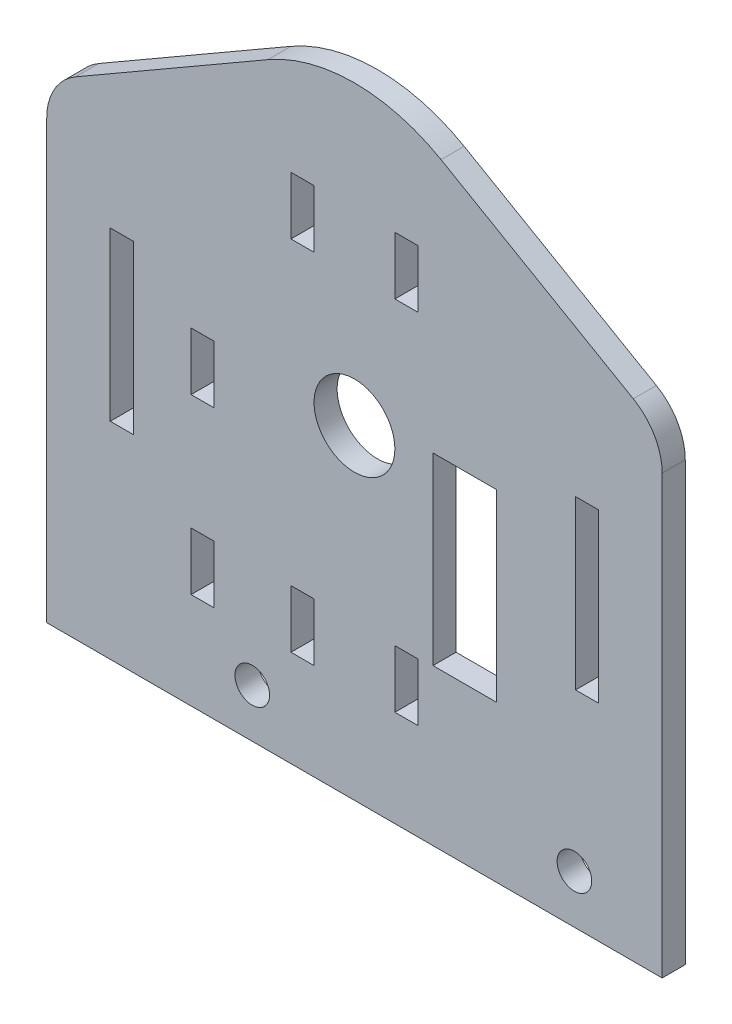
SolidWorks part; units mm, degrees
ref_plane "Front Plane" through (0, 0, 0) normal (0, 0, 1) x (1, 0, 0)
ref_plane "Top Plane" through (0, 0, 0) normal (0, 1, 0) x (1, 0, 0)
ref_plane "Right Plane" through (0, 0, 0) normal (1, 0, 0) x (0, 0, -1)
sketch "Sketch1" plane through (0, 0, 0) normal (0, 0, 1) x (1, 0, 0)
  line L0 (0, 116.93) -> (0, 0) construction
  line L1 (-25.65, 0) -> (25.65, 0)
  line L2 (-26.65, 0) -> (-26.65, 116.93) construction
  line L3 (-26.65, 116.93) -> (26.65, 116.93) construction
  line L4 (26.65, 0) -> (26.65, 116.93) construction
  line L5 (24.15, 104.0845) -> (7.5, 113.6974)
  line L6 (3.5, 106.25) -> (5.5, 106.25)
  line L7 (3.5, 106.25) -> (3.5, 101.25)
  line L8 (3.5, 101.25) -> (5.5, 101.25)
  line L9 (5.5, 106.25) -> (5.5, 101.25)
  line L10 (6.8, 91.35) -> (12.3, 91.35)
  line L11 (6.8, 91.35) -> (6.8, 75.4)
  line L12 (6.8, 75.4) -> (12.3, 75.4)
  line L13 (12.3, 91.35) -> (12.3, 75.4)
  line L14 (19.15, 94.25) -> (21.15, 94.25)
  line L15 (19.15, 94.25) -> (19.15, 79.75)
  line L16 (19.15, 79.75) -> (21.15, 79.75)
  line L17 (21.15, 94.25) -> (21.15, 79.75)
  line L18 (3.5, 75.25) -> (5.5, 75.25)
  line L19 (3.5, 75.25) -> (3.5, 70.25)
  line L20 (3.5, 70.25) -> (5.5, 70.25)
  line L21 (5.5, 75.25) -> (5.5, 70.25)
  line L22 (-7.5, 113.6974) -> (-24.15, 104.0845)
  line L23 (-26.65, 99.7544) -> (-26.65, 1)
  line L24 (26.65, 1) -> (26.65, 99.7544)
  line L25 (-5.5, 75.25) -> (-5.5, 70.25)
  line L26 (-3.5, 75.25) -> (-3.5, 70.25)
  line L27 (-3.5, 75.25) -> (-5.5, 75.25)
  line L28 (-3.5, 70.25) -> (-5.5, 70.25)
  line L29 (-19.15, 94.25) -> (-21.15, 94.25)
  line L30 (-19.15, 79.75) -> (-21.15, 79.75)
  line L31 (-21.15, 94.25) -> (-21.15, 79.75)
  line L32 (-19.15, 94.25) -> (-19.15, 79.75)
  line L33 (-3.5, 101.25) -> (-5.5, 101.25)
  line L34 (-3.5, 106.25) -> (-5.5, 106.25)
  line L35 (-3.5, 106.25) -> (-3.5, 101.25)
  line L36 (-5.5, 106.25) -> (-5.5, 101.25)
  line L37 (-21.15, 92.25) -> (-5.8071, 92.25) construction
  line L38 (-12.15, 70.25) -> (-14.15, 70.25)
  line L39 (-12.15, 70.25) -> (-12.15, 75.25)
  line L40 (-12.15, 75.25) -> (-14.15, 75.25)
  line L41 (-14.15, 70.25) -> (-14.15, 75.25)
  line L42 (-14.15, 85.25) -> (-12.15, 85.25)
  line L43 (-14.15, 85.25) -> (-14.15, 90.25)
  line L44 (-14.15, 90.25) -> (-12.15, 90.25)
  line L45 (-12.15, 85.25) -> (-12.15, 90.25)
  line L46 (-21.15, 82.4202) -> (-6.2517, 82.4202) construction
  line L47 (-8.85, 66.1) -> (19.05, 66.1) construction
  line L48 (0, 34.3) -> (-24.05, 34.3) construction
  line L49 (-20, 34.3) -> (-20, 36.05)
  line L50 (-7, 36.05) -> (-20, 36.05)
  line L51 (-7, 36.05) -> (-7, 34.3)
  line L52 (-7, 34.3) -> (-7, 32.55)
  line L53 (-7, 32.55) -> (-20, 32.55)
  line L54 (-20, 32.55) -> (-20, 34.3)
  line L55 (0, 34.3) -> (-13.6195, 57.8897) construction
  line L56 (-5.2321, 39.3622) -> (-15.7321, 57.5487)
  line L57 (-15.7321, 57.5487) -> (-12.2679, 59.5487)
  line L58 (-12.2679, 59.5487) -> (-1.7679, 41.3622)
  line L59 (-1.7679, 41.3622) -> (-5.2321, 39.3622)
  line L60 (-14, 58.5487) -> (-3.5, 40.3622) construction
  line L61 (1.7679, 41.3622) -> (5.2321, 39.3622)
  line L62 (15.7321, 57.5487) -> (12.2679, 59.5487)
  line L63 (12.2679, 59.5487) -> (1.7679, 41.3622)
  line L64 (5.2321, 39.3622) -> (15.7321, 57.5487)
  line L65 (7, 34.3) -> (7, 32.55)
  line L78 (7, 36.05) -> (7, 34.3)
  line L131 (7, 32.55) -> (20, 32.55)
  line L132 (20, 32.55) -> (20, 34.3)
  line L133 (20, 34.3) -> (20, 36.05)
  line L134 (7, 36.05) -> (20, 36.05)
  line L135 (-1.7679, 27.2378) -> (-5.2321, 29.2378)
  line L136 (-15.7321, 11.0513) -> (-12.2679, 9.0513)
  line L137 (-5.2321, 29.2378) -> (-15.7321, 11.0513)
  line L138 (-12.2679, 9.0513) -> (-1.7679, 27.2378)
  line L139 (15.7321, 11.0513) -> (12.2679, 9.0513)
  line L140 (1.7679, 27.2378) -> (5.2321, 29.2378)
  line L141 (5.2321, 29.2378) -> (15.7321, 11.0513)
  line L142 (12.2679, 9.0513) -> (1.7679, 27.2378)
  circle A2 centre (0, 90) radius 3.5
  arc A3 (-7.5, 113.6974) -> (7.5, 113.6974) centre (0, 100.707) cw
  arc A4 (26.65, 99.7544) -> (24.15, 104.0845) centre (21.65, 99.7544) ccw
  arc A5 (-24.15, 104.0845) -> (-26.65, 99.7544) centre (-21.65, 99.7544) ccw
  arc A6 (25.65, 0) -> (26.65, 1) centre (25.65, 1) ccw
  arc A7 (-25.65, 0) -> (-26.65, 1) centre (-25.65, 1) cw
  circle A8 centre (19.05, 66.1) radius 1.5
  circle A9 centre (-8.85, 66.1) radius 1.5
  circle A10 centre (-24.05, 15.3) radius 1.5
  circle A11 centre (24.15, 14) radius 1.5
  circle A12 centre (0, 34.3) radius 2.5
  circle A22 centre (0, 34.3) radius 7 construction
  point P35 (26.65, 102.6412)
  point P50 (-26.65, 102.6412)
  point P115 (0, 34.3)
  dimension "D11" = 2
  dimension "D15" = 17
  dimension "D28" = 14
  dimension "D29" = 7
  dimension "D30" = 2.5
  dimension "D47" = 5
  dimension "D48" = 5
  dimension "D49" = 1
  dimension "D50" = 3
  dimension "D51" = 3
  dimension "D52" = 3
  dimension "D53" = 3
  dimension "D16" = 15
  dimension "D31" = 7.6
  dimension "D35" = 66.1
  dimension "D39" = 27.9
  dimension "D40" = 15.2
  dimension "D41" = 5
  dimension "D45" = 14
  dimension "D6" = 26
  dimension "D7" = 5
  dimension "D8" = 2
  dimension "D9" = 5
  dimension "D10" = 10
  dimension "D12" = 9.8298
  dimension "D13" = 2.8298
  dimension "D14" = 5
  dimension "D17" = 53.3
  dimension "D18" = 2
  dimension "D19" = 5.5
  dimension "D20" = 2
  dimension "D21" = 15.3
  dimension "D22" = 14.5
  dimension "D23" = 15.95
  dimension "D24" = 5
  dimension "D25" = 5
  dimension "D26" = 2
  dimension "D27" = 5.5
  dimension "D32" = 6.8
  dimension "D33" = 3.5
  dimension "D34" = 3.5
  dimension "D36" = 90
  dimension "D37" = 60
  dimension "D38" = 60
  dimension "D42" = 14.6
  dimension "D43" = 34.3
  dimension "D44" = 1.75
  dimension "D46" = 10.25
  dimension "D54" = 60
  dimension "D55" = 4
  dimension "D56" = 3.5
  dimension "D57" = 21
  dimension "D58" = 13
extrude "Boss-Extrude1" add sketch "Sketch1" along normal blind 2
sketch "草图1" plane through (0, 0, 0) normal (0, 0, -1) x (-1, 0, 0)
  line L0 (-26.65, 61.8922) -> (26.65, 61.8922)
  line L1 (-26.65, 1) -> (-26.65, 99.7544) construction
  line L2 (26.65, 99.7544) -> (26.65, 1) construction
  line L3 (26.65, 61.8922) -> (26.65, 1)
  line L4 (26.65, 1) -> (26.65, 0)
  line L5 (26.65, 0) -> (-26.65, 0)
  line L6 (-26.65, 0) -> (-26.65, 61.8922)
extrude "切除-拉伸1" cut sketch "草图1" against normal blind 10
